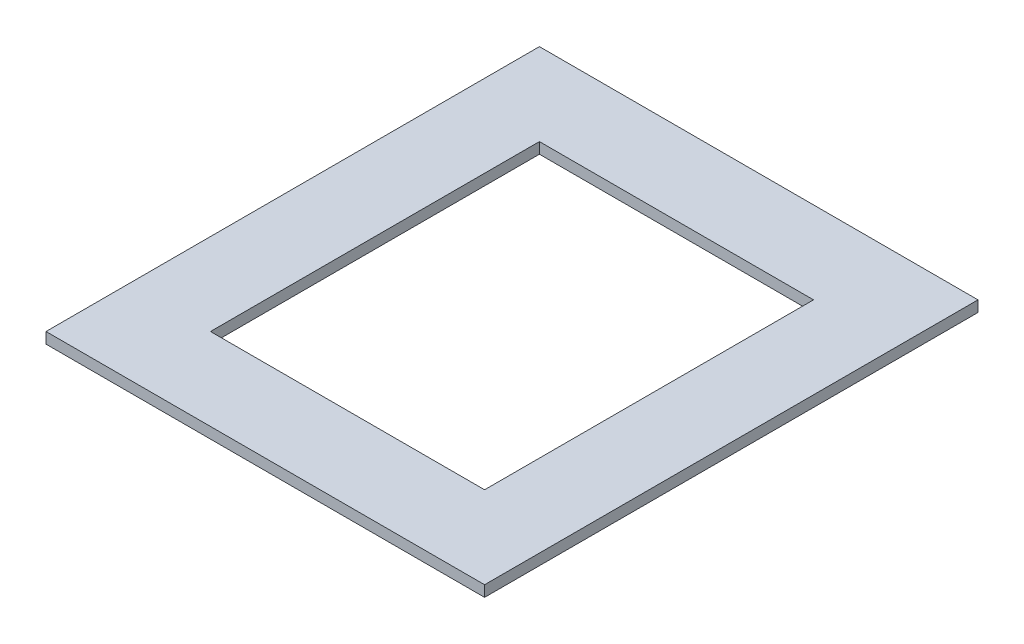
SolidWorks part; units mm, degrees
material "Balsa"
ref_plane "Plan de face" through (0, 0, 0) normal (0, 0, 1) x (1, 0, 0)
ref_plane "Plan de dessus" through (0, 0, 0) normal (0, 1, 0) x (1, 0, 0)
ref_plane "Plan de droite" through (0, 0, 0) normal (1, 0, 0) x (0, 0, -1)
sketch "Esquisse1" plane through (0, 0, 0) normal (0, 1, 0) x (1, 0, 0)
  line L1 (0, 0) -> (-400, 0)
  line L2 (0, 0) -> (0, 450)
  line L3 (0, 450) -> (-400, 450)
  line L4 (-400, 0) -> (-400, 450)
  dimension "D1" = 400
  dimension "D2" = 450
extrude "Boss.-Extru.1" add sketch "Esquisse1" along normal blind 10
sketch "Esquisse2" plane through (0, 10, 0) normal (0, 1, 0) x (1, 0, 0)
  line L0 (-400, 450) -> (-400, 0) construction
  line L1 (-325, 75) -> (-75, 75)
  line L2 (-325, 75) -> (-325, 375)
  line L3 (-325, 375) -> (-75, 375)
  line L4 (-75, 75) -> (-75, 375)
  line L5 (-400, 0) -> (0, 0) construction
  line L6 (0, 0) -> (0, 450) construction
  line L7 (0, 450) -> (-400, 450) construction
  dimension "D1" = 75
  dimension "D2" = 75
  dimension "D3" = 75
  dimension "D4" = 75
extrude "Enlèv. mat.-Extru.1" cut sketch "Esquisse2" against normal blind 10
